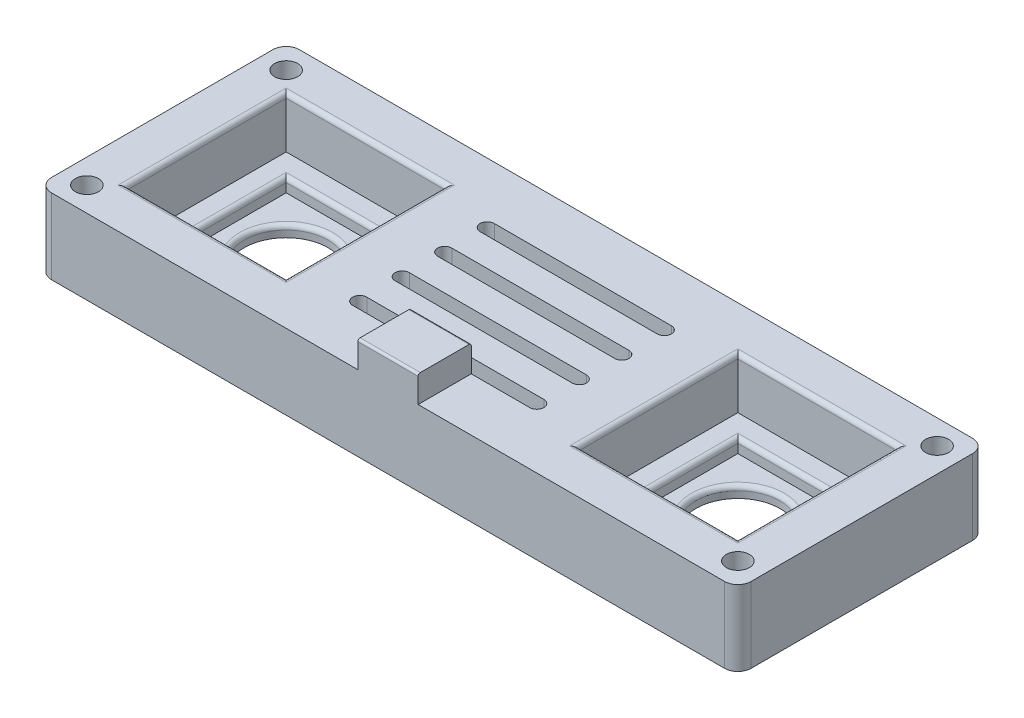
SolidWorks part; units mm, degrees
ref_plane "Front Plane" through (0, 0, 0) normal (0, 0, 1) x (1, 0, 0)
ref_plane "Top Plane" through (0, 0, 0) normal (0, 1, 0) x (1, 0, 0)
ref_plane "Right Plane" through (0, 0, 0) normal (1, 0, 0) x (0, 0, -1)
sketch "Sketch1" plane through (0, 0, 0) normal (0, 1, 0) x (1, 0, 0)
  line L1 (-79, 28) -> (79, 28)
  line L2 (-79, 28) -> (-79, -28)
  line L3 (-79, -28) -> (79, -28)
  line L4 (79, 28) -> (79, -28)
  line L5 (-79, 28) -> (79, -28) construction
  line L6 (-79, -28) -> (79, 28) construction
  point P0 (0, 0)
  dimension "D1" = 56
  dimension "D2" = 158
extrude "Boss-Extrude1" add sketch "Sketch1" along normal blind 17
sketch "Sketch8" plane through (0, 17, 0) normal (0, 1, 0) x (1, 0, 0)
  line L0 (0, 42.5656) -> (0, -55.7728) construction
  line L1 (-6.8, -28) -> (6.8, -28)
  line L2 (-79, -28) -> (79, -28) construction
  line L3 (6.8, -28) -> (6.8, -16)
  line L4 (6.8, -16) -> (-6.8, -16)
  line L5 (-6.8, -28) -> (-6.8, -16)
  point P10 (0, -28)
  point P11 (0, -16)
  dimension "D1" = 6.8
  dimension "D2" = 12
extrude "Boss-Extrude2" add sketch "Sketch8" along normal blind 6
sketch "Sketch2" plane through (0, 17, 0) normal (0, 1, 0) x (1, 0, 0)
  line L0 (0, 45.0934) -> (0, -55.517) construction
  line L1 (-92.1507, 0) -> (93.0571, 0) construction
  line L2 (-79, 28) -> (-79, -28) construction
  line L3 (-69, 18) -> (-33, 18)
  line L4 (-69, 18) -> (-69, -18)
  line L5 (-69, -18) -> (-33, -18)
  line L6 (-33, 18) -> (-33, -18)
  line L7 (-69, 18) -> (-33, -18) construction
  line L8 (-69, -18) -> (-33, 18) construction
  line L9 (69, -18) -> (33, -18)
  line L10 (33, 18) -> (33, -18)
  line L11 (69, 18) -> (33, 18)
  line L12 (69, 18) -> (69, -18)
  point P5 (-51, 0)
  dimension "D1" = 36
  dimension "D2" = 36
  dimension "D3" = 10
extrude "Cut-Extrude1" cut sketch "Sketch2" against normal blind 11.5
sketch "Sketch3" plane through (0, 5.5, 0) normal (0, 1, 0) x (1, 0, 0)
  line L0 (0, 43.4317) -> (0, -55.8191) construction
  line L1 (-105.1424, 0) -> (93.6613, 0) construction
  line L6 (38, 13) -> (64, 13)
  line L7 (38, -13) -> (38, 13)
  line L8 (64, -13) -> (38, -13)
  line L9 (64, 13) -> (64, -13)
  line L10 (-64, 13) -> (-64, -13)
  line L11 (-64, -13) -> (-38, -13)
  line L12 (-38, -13) -> (-38, 13)
  line L13 (-38, 13) -> (-64, 13)
  line L14 (-64, 13) -> (-64, -13)
  line L15 (-64, -13) -> (-38, -13)
  line L16 (-38, -13) -> (-38, 13)
  line L17 (-38, 13) -> (-64, 13)
  dimension "D1" = 5
extrude "Cut-Extrude2" cut sketch "Sketch3" against normal blind 3
sketch "Sketch4" plane through (0, 2.5, 0) normal (0, 1, 0) x (1, 0, 0)
  line L0 (0, 41.6189) -> (0, -60.2001) construction
  line L1 (-103.6317, 0) -> (106.0488, 0) construction
  line L2 (-51, 13) -> (-51, 0) construction
  line L3 (-38, 13) -> (-64, 13) construction
  circle A0 centre (-51, 0) radius 9.5
  circle A1 centre (51, 0) radius 9.5
  dimension "D1" = 19
extrude "Cut-Extrude3" cut sketch "Sketch4" against normal up to next
sketch "Sketch5" plane through (0, 17, 0) normal (0, 1, 0) x (1, 0, 0)
  line L0 (-79, 28) -> (-69, 18) construction
  line L1 (79, 28) -> (-79, 28) construction
  line L2 (0, 35.6822) -> (0, -33.3549) construction
  line L3 (-97.0967, 0) -> (95.9932, 0) construction
  circle A0 centre (-73.5, 22.5) radius 2.6
  circle A2 centre (73.5, 22.5) radius 2.6
  circle A3 centre (73.5, -22.5) radius 2.6
  circle A4 centre (-73.5, -22.5) radius 2.6
  dimension "D1" = 5.5
  dimension "D2" = 5.2
extrude "Cut-Extrude4" cut sketch "Sketch5" against normal blind 4.5
sketch "Sketch6" plane through (0, 17, 0) normal (0, 1, 0) x (1, 0, 0)
  line L0 (-20, 4.8) -> (20, 4.8) construction
  line L1 (-20, 6.4) -> (20, 6.4)
  line L2 (-20, 3.2) -> (20, 3.2)
  line L3 (-28.0094, 0) -> (25.6485, 0) construction
  line L4 (-20, -4.8) -> (20, -4.8) construction
  line L7 (-20, 14.4) -> (20, 14.4) construction
  line L8 (-20, 16) -> (20, 16)
  line L9 (-20, 12.8) -> (20, 12.8)
  line L10 (-20, -6.4) -> (20, -6.4)
  line L11 (-20, -3.2) -> (20, -3.2)
  line L12 (-20, -14.4) -> (20, -14.4) construction
  line L13 (-20, -16) -> (20, -16)
  line L14 (-20, -12.8) -> (20, -12.8)
  arc A0 (-20, 6.4) -> (-20, 3.2) centre (-20, 4.8) ccw
  arc A1 (20, 3.2) -> (20, 6.4) centre (20, 4.8) ccw
  arc A4 (-20, 16) -> (-20, 12.8) centre (-20, 14.4) ccw
  arc A5 (20, 12.8) -> (20, 16) centre (20, 14.4) ccw
  arc A6 (-20, -6.4) -> (-20, -3.2) centre (-20, -4.8) cw
  arc A7 (20, -3.2) -> (20, -6.4) centre (20, -4.8) cw
  arc A8 (-20, -16) -> (-20, -12.8) centre (-20, -14.4) cw
  arc A9 (20, -12.8) -> (20, -16) centre (20, -14.4) cw
  point P2 (0, 4.8)
  point P12 (0, -4.8)
  point P20 (0, 14.4)
  point P26 (0, -14.4)
  dimension "D2" = 1.6
  dimension "D1" = 40
  dimension "D3" = 4.8
  dimension "D5" = 9.6
  dimension "D4" = 2
extrude "Cut-Extrude5" cut sketch "Sketch6" against normal up to next
fillet "Fillet1" radius 3 4 edges at (-79, 8.5, 28) (79, 8.5, 28) (-79, 8.5, -28) (79, 8.5, -28)
fillet "Fillet2" radius 1 2 edges at (51, 2.5, -9.5) (-51, 2.5, 9.5)
fillet "Fillet3" radius 1 8 edges at (51, 5.5, 13) (64, 5.5, 0) (51, 5.5, -13) (38, 5.5, 0) (-51, 5.5, 13) (-38, 5.5, 0) (-64, 5.5, 0) (-51, 5.5, -13)
fillet "Fillet4" radius 1 8 edges at (51, 17, -18) (33, 17, 0) (51, 17, 18) (69, 17, 0) (-51, 17, 18) (-33, 17, 0) (-51, 17, -18) (-69, 17, 0)
fillet "Fillet5" radius 0.5 2 edges at (0, 23, 28) (0, 23, 16)
